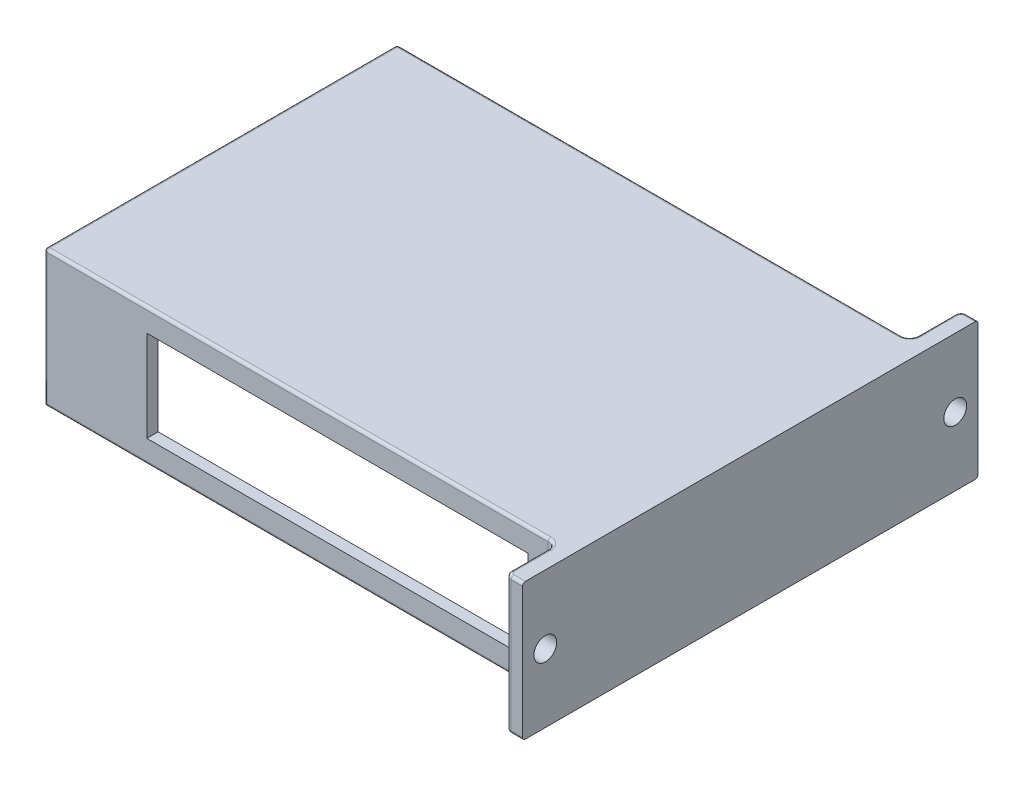
SolidWorks part; units mm, degrees
ref_plane "Ebene vorne" through (0, 0, 0) normal (0, 0, 1) x (1, 0, 0)
ref_plane "Ebene oben" through (0, 0, 0) normal (0, 1, 0) x (1, 0, 0)
ref_plane "Ebene rechts" through (0, 0, 0) normal (1, 0, 0) x (0, 0, -1)
ref_plane "Ebene1" through (0, 0, 0) normal (0, 0, 1) x (1, 0, 0)
ref_plane "Ebene2" through (0, 0, 0) normal (0, 1, 0) x (1, 0, 0)
ref_plane "Ebene3" through (0, 0, 0) normal (1, 0, 0) x (0, 0, -1)
sketch "Skizze1" plane through (0, 0, 0) normal (0, 0, 1) x (1, 0, 0)
  line L1 (0, 0) -> (-90, 0)
  line L2 (0, 0) -> (0, 24)
  line L3 (0, 24) -> (-90, 24)
  line L4 (-90, 0) -> (-90, 24)
  dimension "D1" = 90
  dimension "D2" = 24
extrude "Aufsatz-Linear austragen1" add sketch "Skizze1" against normal blind 62
sketch "Skizze2" plane through (0, 0, 0) normal (0, -1, 0) x (1, 0, 0)
  line L0 (0, -55) -> (0, 55) construction
  line L1 (-2, -60) -> (-88, -60)
  line L2 (-2, -60) -> (-2, -2)
  line L3 (-2, -2) -> (-88, -2)
  line L4 (-88, -60) -> (-88, -2)
  line L5 (-90, -62) -> (0, -62) construction
  line L7 (-90, 0) -> (0, 0) construction
  line L8 (-90, -62) -> (-90, 0) construction
  dimension "D1" = 2
  dimension "D2" = 2
  dimension "D3" = 2
  dimension "D4" = 2
extrude "Schnitt-Linear austragen1" cut sketch "Skizze2" against normal blind 22
sketch "Skizze3" plane through (-90, 0, 0) normal (-1, 0, 0) x (0, 0, 1)
  line L0 (-62, 24) -> (0, 24) construction
  line L1 (-2, 0) -> (-60, 0)
  line L2 (-2, 0) -> (-2, 20)
  line L3 (-2, 20) -> (-60, 20)
  line L4 (-60, 0) -> (-60, 20)
  line L5 (0, -55) -> (0, 55) construction
  line L6 (-62, 24) -> (-62, 0) construction
  line L7 (-62, 0) -> (0, 0) construction
  dimension "D1" = 4
  dimension "D2" = 2
  dimension "D3" = 2
  dimension "D4" = 0
extrude "Schnitt-Linear austragen2" cut sketch "Skizze3" against normal blind 5
sketch "Skizze4" plane through (0, 0, 0) normal (0, 0, 1) x (1, 0, 0)
  line L0 (0, 0) -> (0, 24) construction
  line L1 (-5, 4) -> (-72, 4)
  line L2 (-5, 4) -> (-5, 20)
  line L3 (-5, 20) -> (-72, 20)
  line L4 (-72, 4) -> (-72, 20)
  line L5 (0, 24) -> (-90, 24) construction
  line L6 (-90, 0) -> (0, 0) construction
  line L7 (-90, 24) -> (-90, 0) construction
  dimension "D1" = 5
  dimension "D2" = 4
  dimension "D3" = 4
  dimension "D4" = 18
extrude "Schnitt-Linear austragen3" cut sketch "Skizze4" against normal blind 50
sketch "Skizze5" plane through (0, 0, 0) normal (1, 0, 0) x (0, 0, -1)
  line L6 (62, 0) -> (0, 0) construction
  circle A0 centre (67, 12) radius 2
  circle A1 centre (-5, 12) radius 2
  point P10 (31, 0)
  dimension "D1" = 72
  dimension "D2" = 36
sketch "Skizze6" plane through (0, 0, 0) normal (0, 1, 0) x (1, 0, 0)
  line L1 (0, -9) -> (3, -9)
  line L2 (0, -9) -> (0, 71)
  line L3 (0, 71) -> (3, 71)
  line L4 (3, -9) -> (3, 71)
  dimension "D1" = 80
  dimension "D2" = 9
  dimension "D3" = 3
extrude "Aufsatz-Linear austragen2" add sketch "Skizze6" along normal blind 24
extrude "Schnitt-Linear austragen6" cut sketch "Skizze5" along normal blind 24
fillet "Verrundung1" radius 1.5 2 edges at (0, 12, 0) (0, 12, -62)
fillet "Verrundung2" radius 1 2 edges at (0, 12, 9) (0, 12, -71)
fillet "Verrundung3" radius 0.5 23 edges at (0.2929, 0, -70.7071) (0.2929, 24, -70.7071) (-45.75, 0, 0) (2, 0, -71) (2, 24, -71) (0.2929, 24, 8.7071) (2, 24, 9) (2, 0, 9) (-0.4393, 24, 0.4393) (0, 0, 4.75) (0, 24, 4.75) (0, 24, -66.75) (0, 0, -66.75) (-0.4393, 24, -62.4393) (-0.4393, 0, -62.4393) (0.2929, 0, 8.7071) (-0.4393, 0, 0.4393) (-45.75, 24, 0) (-90, 12, 0) (-45.75, 24, -62) (-90, 24, -31) (-90, 12, -62) (-45.75, 0, -62)
